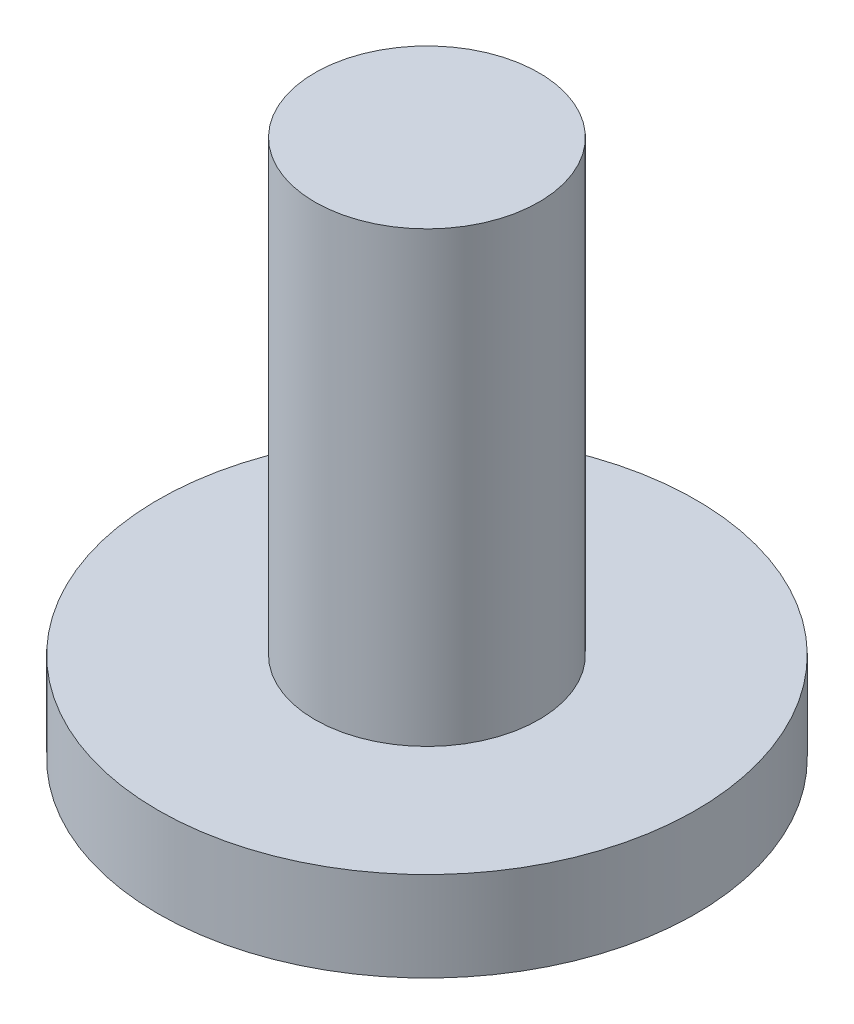
SolidWorks part; units mm, degrees
material "Aleación 1060"
ref_plane "Alzado" through (0, 0, 0) normal (0, 0, 1) x (1, 0, 0)
ref_plane "Planta" through (0, 0, 0) normal (0, 1, 0) x (1, 0, 0)
ref_plane "Vista lateral" through (0, 0, 0) normal (1, 0, 0) x (0, 0, -1)
sketch "Croquis1" plane through (0, 0, 0) normal (0, 1, 0) x (1, 0, 0)
  circle A0 centre (0, 0) radius 6
  dimension "D1" = 12
extrude "Saliente-Extruir1" add sketch "Croquis1" along normal blind 2
sketch "Croquis2" plane through (0, 2, 0) normal (0, 1, 0) x (1, 0, 0)
  circle A0 centre (0, 0) radius 2.5
  dimension "D1" = 5
extrude "Saliente-Extruir2" add sketch "Croquis2" along normal blind 10
